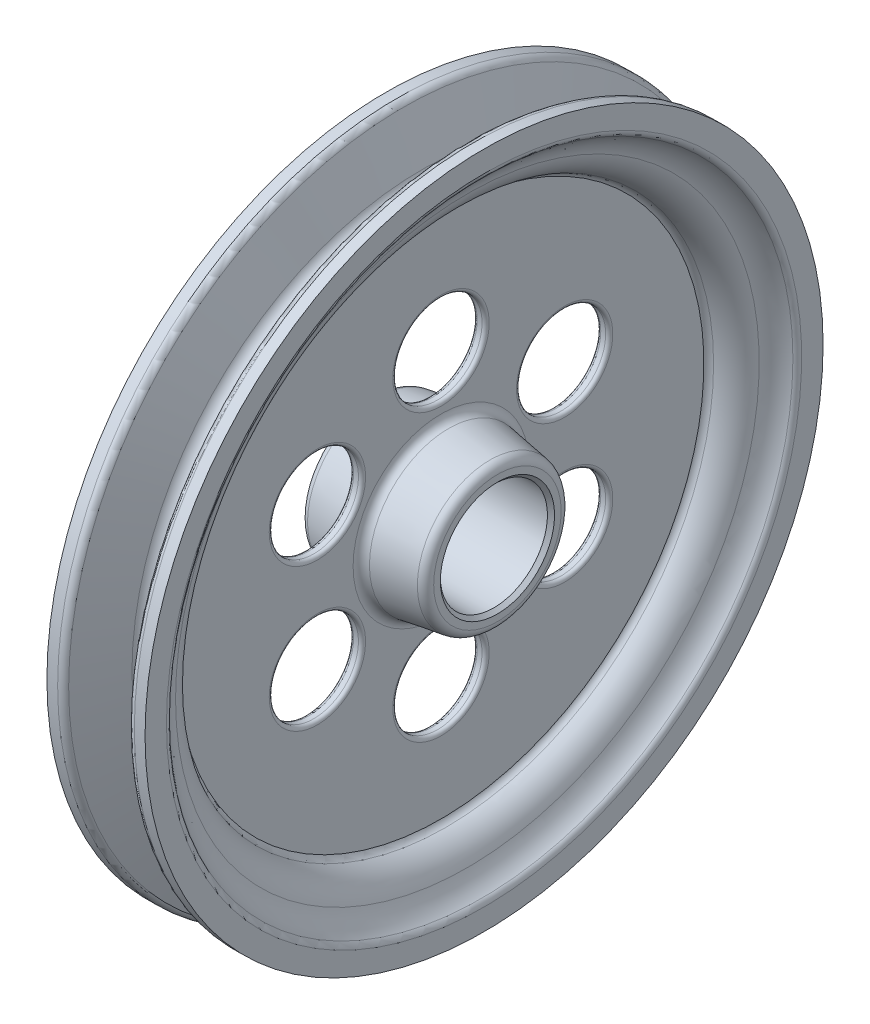
SolidWorks part; units mm, degrees
ref_plane "Front Plane" through (0, 0, 0) normal (0, 0, 1) x (1, 0, 0)
ref_plane "Top Plane" through (0, 0, 0) normal (0, 1, 0) x (1, 0, 0)
ref_plane "Right Plane" through (0, 0, 0) normal (1, 0, 0) x (0, 0, -1)
sketch "Sketch1" plane through (0, 0, 0) normal (0, 0, 1) x (1, 0, 0)
  line L0 (-48.978, 30) -> (24.4605, 30) construction
  line L1 (0, -14.8906) -> (0, 117.4823) construction
  line L2 (33, 30) -> (-33, 30)
  line L3 (-35, 32) -> (-35, 35.7284)
  line L4 (-30.7808, 40.6671) -> (-7.5942, 44.3329)
  line L5 (-3.375, 49.2716) -> (-3.375, 147.3225)
  line L6 (-33, 30) -> (-35, 32)
  line L7 (-94.4509, 0) -> (67.3577, 0) construction
  line L8 (-27.5, 178) -> (-27.5, 190)
  line L9 (-9.5322, 165.5) -> (11.8175, 165.5) construction
  line L10 (-7.391, 162.4385) -> (-17.7846, 187.5307)
  line L11 (-27.5, 190) -> (-21.4801, 190)
  line L12 (-37.5, 182.8657) -> (-37.5, 153.2986) construction
  line L13 (33, 30) -> (35, 32)
  line L14 (35, 32) -> (35, 35.7284)
  line L15 (30.7808, 40.6671) -> (7.5942, 44.3329)
  line L16 (3.375, 49.2716) -> (3.375, 147.3225)
  line L17 (27.5, 178) -> (27.5, 190)
  line L18 (27.5, 190) -> (21.4801, 190)
  line L19 (7.391, 162.4385) -> (17.7846, 187.5307)
  arc A0 (-7.5942, 44.3329) -> (-3.375, 49.2716) centre (-8.375, 49.2716) ccw
  arc A1 (-35, 35.7284) -> (-30.7808, 40.6671) centre (-30, 35.7284) cw
  arc A2 (-3.375, 147.3225) -> (-6.1343, 150) centre (-7.9689, 145.3488) ccw
  arc A3 (-6.1343, 150) -> (-18.1479, 163.5557) centre (1.2042, 168.605) cw
  arc A4 (-18.1479, 163.5557) -> (-25.8333, 174.7511) centre (-37.5, 158.5064) ccw
  arc A5 (-25.8333, 174.7511) -> (-27.5, 178) centre (-23.5, 178) cw
  arc A6 (-7.391, 162.4385) -> (7.391, 162.4385) centre (0, 165.5) ccw
  arc A7 (-21.4801, 190) -> (-17.7846, 187.5307) centre (-21.4801, 186) cw
  arc A8 (35, 35.7284) -> (30.7808, 40.6671) centre (30, 35.7284) ccw
  arc A9 (7.5942, 44.3329) -> (3.375, 49.2716) centre (8.375, 49.2716) cw
  arc A10 (3.375, 147.3225) -> (6.1343, 150) centre (7.9689, 145.3488) cw
  arc A11 (6.1343, 150) -> (18.1479, 163.5557) centre (-1.2042, 168.605) ccw
  arc A12 (18.1479, 163.5557) -> (25.8333, 174.7511) centre (37.5, 158.5064) cw
  arc A13 (25.8333, 174.7511) -> (27.5, 178) centre (23.5, 178) ccw
  arc A14 (21.4801, 190) -> (17.7846, 187.5307) centre (21.4801, 186) ccw
  point P5 (0, 30)
  point P7 (-35, 30)
  point P15 (-3.375, 45)
  point P18 (-35, 40)
  point P32 (0, 165.5)
  point P42 (0, 30)
  dimension "D6" = 5
  dimension "D9" = 190
  dimension "D11" = 5
  dimension "D12" = 20
  dimension "D13" = 20
  dimension "D14" = 4
  dimension "D18" = 22.5
  dimension "D19" = 16
  dimension "D20" = 4
  dimension "D1" = 30
  dimension "D2" = 40
  dimension "D3" = 45
  dimension "D4" = 2
  dimension "D5" = 45
  dimension "D7" = 6.75
  dimension "D8" = 150
  dimension "D10" = 35
  dimension "D15" = 12
  dimension "D16" = 27.5
  dimension "D17" = 24.5
  dimension "D21" = 10
revolve "Revolve1" add sketch "Sketch1" angle 360 about L7
sketch "Sketch2" plane through (0, 0, 0) normal (1, 0, 0) x (0, 0, -1)
  line L0 (0, 23.3031) -> (0, 199.4852) construction
  circle A0 centre (0, 0) radius 80 construction
  circle A1 centre (0, 80) radius 25
  circle A2 centre (69.282, 40) radius 25
  circle A3 centre (69.282, -40) radius 25
  circle A4 centre (0, -80) radius 25
  circle A5 centre (-69.282, -40) radius 25
  circle A6 centre (-69.282, 40) radius 25
  point P4 (0, 80)
  point P22 (0, 0)
  dimension "D1" = 160
  dimension "D2" = 50
  dimension "D3" = 6
extrude "Cut-Extrude2" cut sketch "Sketch2" along normal mid plane 10
fillet "Fillet1" radius 2 12 edges at (3.375, 40, -44.282) (3.375, 80, 25) (3.375, 40, 94.282) (3.375, -40, 94.282) (3.375, -80, 25) (3.375, -40, -44.282) (-3.375, 40, 44.282) (-3.375, -40, 44.282) (-3.375, -80, -25) (-3.375, 80, -25) (-3.375, 40, -94.282) (-3.375, -40, -94.282)
